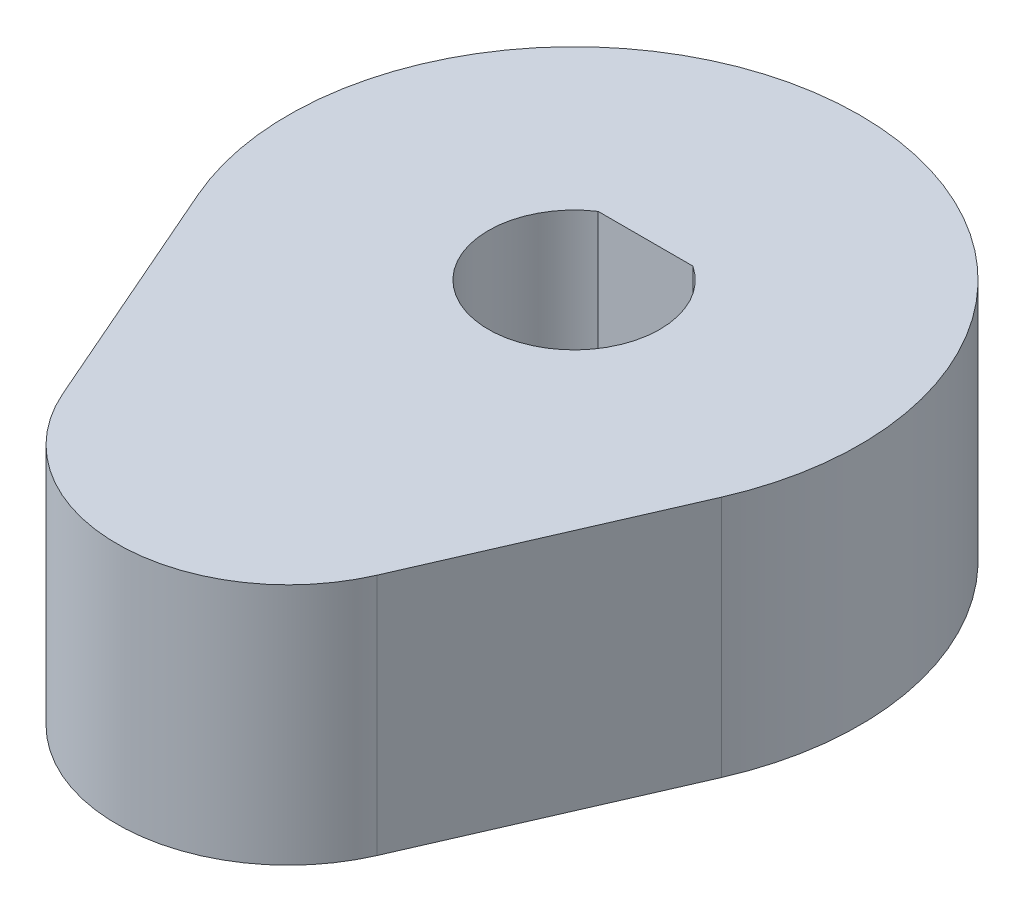
SolidWorks part; units mm, degrees
material "PET"
ref_plane "Front Plane" through (0, 0, 0) normal (0, 0, 1) x (1, 0, 0)
ref_plane "Top Plane" through (0, 0, 0) normal (0, 1, 0) x (1, 0, 0)
ref_plane "Right Plane" through (0, 0, 0) normal (1, 0, 0) x (0, 0, -1)
sketch "Sketch1" plane through (0, 0, 0) normal (0, 1, 0) x (1, 0, 0)
  line L0 (1.6583, 2.5) -> (-1.6583, 2.5)
  line L6 (0, 0) -> (0, -10) construction
  line L7 (-9.1652, -4) -> (-5.4991, -12.4)
  line L8 (9.1652, -4) -> (5.4991, -12.4)
  arc A0 (-1.6583, 2.5) -> (1.6583, 2.5) centre (0, 0) ccw
  arc A3 (9.1652, -4) -> (-9.1652, -4) centre (0, 0) ccw
  arc A4 (-5.4991, -12.4) -> (5.4991, -12.4) centre (0, -10) ccw
  dimension "D1" = 6
  dimension "D4" = 12
  dimension "D3" = 20
  dimension "D2" = 2.5
  dimension "D5" = 10
extrude "Boss-Extrude1" add sketch "Sketch1" along normal blind 8.5
